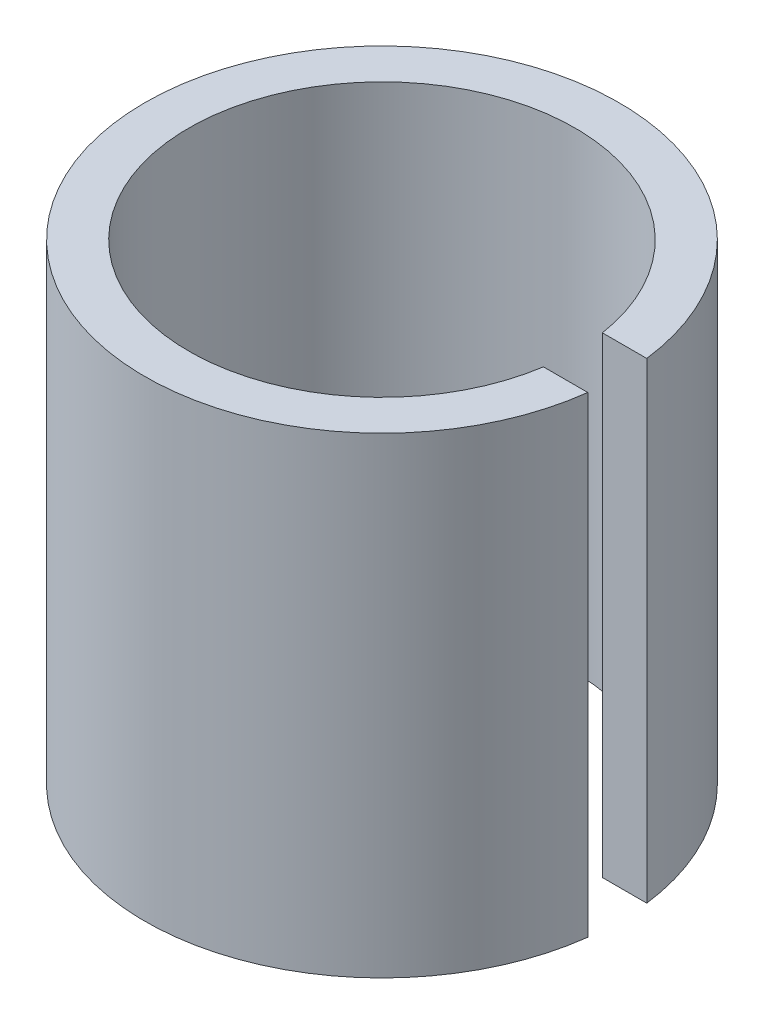
SolidWorks part; units mm, degrees
ref_plane "Front Plane" through (0, 0, 0) normal (0, 0, 1) x (1, 0, 0)
ref_plane "Top Plane" through (0, 0, 0) normal (0, 1, 0) x (1, 0, 0)
ref_plane "Right Plane" through (0, 0, 0) normal (1, 0, 0) x (0, 0, -1)
sketch "Sketch1" plane through (0, 0, 0) normal (0, 1, 0) x (1, 0, 0)
  line L1 (4.8574, -0.75) -> (5.9857, -0.75)
  line L3 (4.8574, 0.75) -> (5.9857, 0.75)
  line L5 (1.415, -0.75) -> (8.415, 0.75) construction
  line L6 (1.415, 0.75) -> (8.415, -0.75) construction
  arc A0 (5.9857, 0.75) -> (5.9857, -0.75) centre (0, 0) ccw
  arc A2 (4.8574, 0.75) -> (4.8574, -0.75) centre (0, 0) ccw
  point P4 (4.915, 0)
extrude "Boss-Extrude1" add sketch "Sketch1" along normal blind 12
